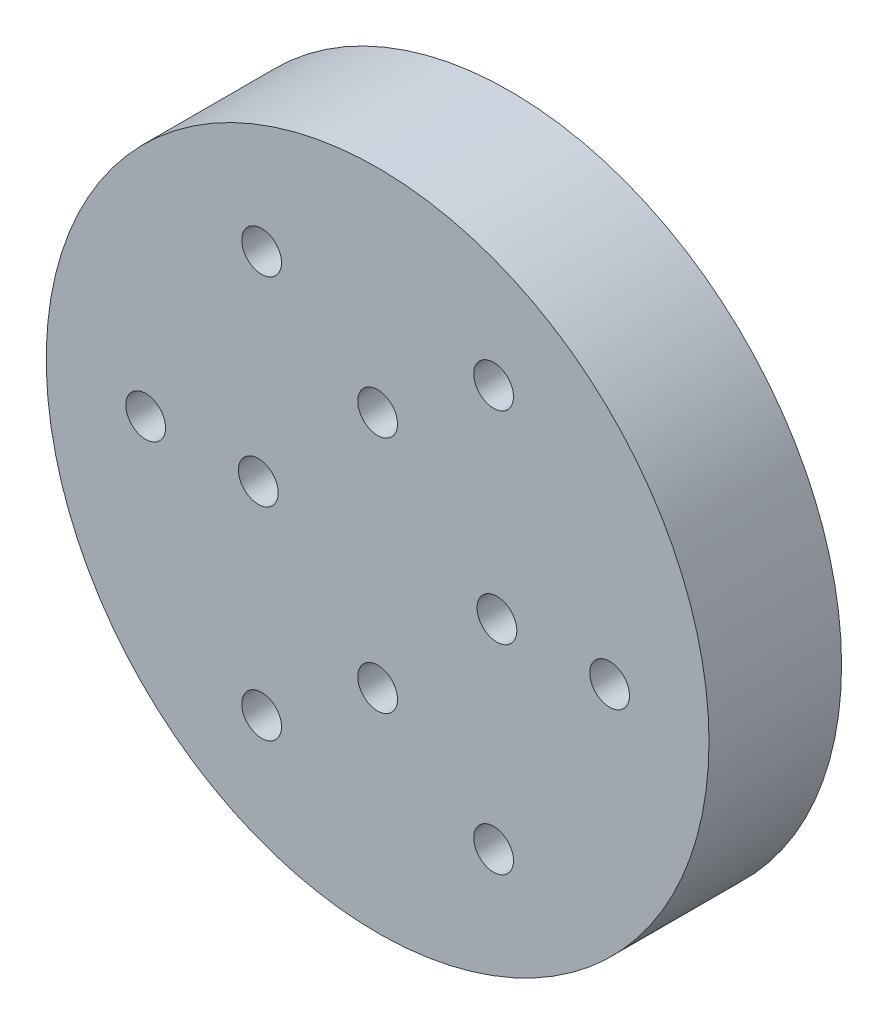
SolidWorks part; units mm, degrees
ref_plane "前视基准面" through (0, 0, 0) normal (0, 0, 1) x (1, 0, 0)
ref_plane "上视基准面" through (0, 0, 0) normal (0, 1, 0) x (1, 0, 0)
ref_plane "右视基准面" through (0, 0, 0) normal (1, 0, 0) x (0, 0, -1)
sketch "草图1" plane through (0, 0, 0) normal (0, 0, 1) x (1, 0, 0)
  circle A0 centre (0, 0) radius 50
  circle A1 centre (0, 0) radius 18
  circle A2 centre (0, 0) radius 35
  circle A3 centre (-18, 0) radius 3
  circle A4 centre (0, 18) radius 3
  circle A5 centre (18, 0) radius 3
  circle A6 centre (0, -18) radius 3
  circle A7 centre (-35, 0) radius 3
  circle A8 centre (-17.5, 30.3109) radius 3
  circle A9 centre (17.5, 30.3109) radius 3
  circle A10 centre (35, 0) radius 3
  circle A11 centre (17.5, -30.3109) radius 3
  circle A12 centre (-17.5, -30.3109) radius 3
  point P15 (0, 0)
  point P28 (0, 0)
  dimension "D1" = 4
  dimension "D2" = 6
extrude "凸台-拉伸1" add sketch "草图1" along normal blind 20 contours A0 A12 A2 A7 A8 A9 A10 A11 | A12 A2 A11 A10 A9 A8 A7 A6 A1 A3 A4 A5 | A6 A1 A5 A4 A3
